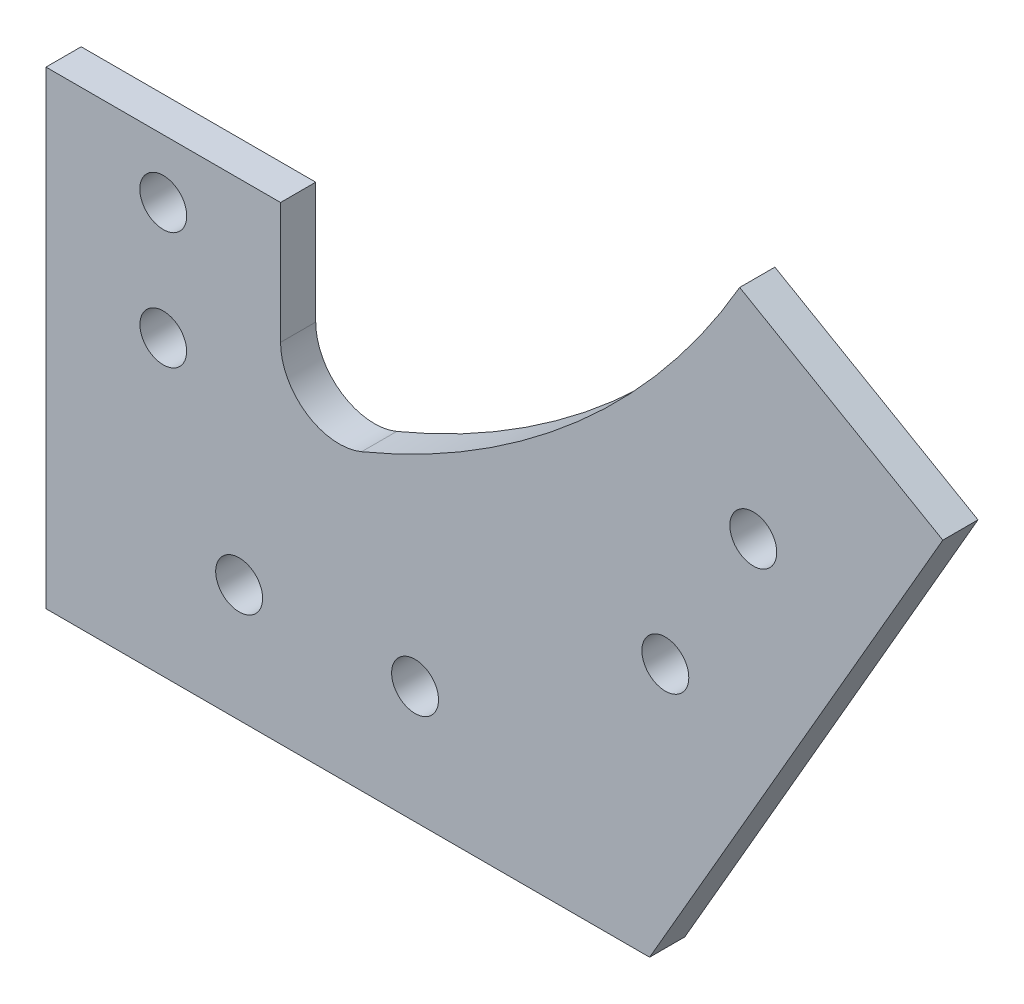
SolidWorks part; units mm, degrees
ref_plane "前视基准面" through (0, 0, 0) normal (0, 0, 1) x (1, 0, 0)
ref_plane "上视基准面" through (0, 0, 0) normal (0, 1, 0) x (1, 0, 0)
ref_plane "右视基准面" through (0, 0, 0) normal (1, 0, 0) x (0, 0, -1)
sketch "草图1" plane through (0, 0, 0) normal (0, 0, 1) x (1, 0, 0)
  line L0 (-16.6515, -45.9842) -> (-16.6515, -35.6551)
  line L1 (-16.6515, -35.6551) -> (-36.6515, -35.6551)
  line L2 (-36.6515, -35.6551) -> (-36.6515, -75.6551)
  line L3 (-36.6515, -75.6551) -> (14.8185, -75.6551)
  line L4 (14.8185, -75.6551) -> (39.8185, -32.3538)
  line L5 (39.8185, -32.3538) -> (22.498, -22.3538)
  circle A0 centre (-26.6515, -40.6551) radius 2
  circle A1 centre (-26.6515, -50.6551) radius 1.99
  arc A2 (-9.7416, -50.605) -> (22.498, -22.3538) centre (-35.1815, 10.9475) ccw
  arc A3 (-16.6515, -45.9842) -> (-9.7416, -50.605) centre (-11.6515, -45.9842) ccw
  circle A4 centre (-20.1815, -65.6551) radius 2
  circle A5 centre (-5.1815, -65.6551) radius 2
  circle A6 centre (16.1583, -53.3345) radius 2
  circle A7 centre (23.6583, -40.3442) radius 2
extrude "凸台-拉伸1" add sketch "草图1" along normal blind 3
